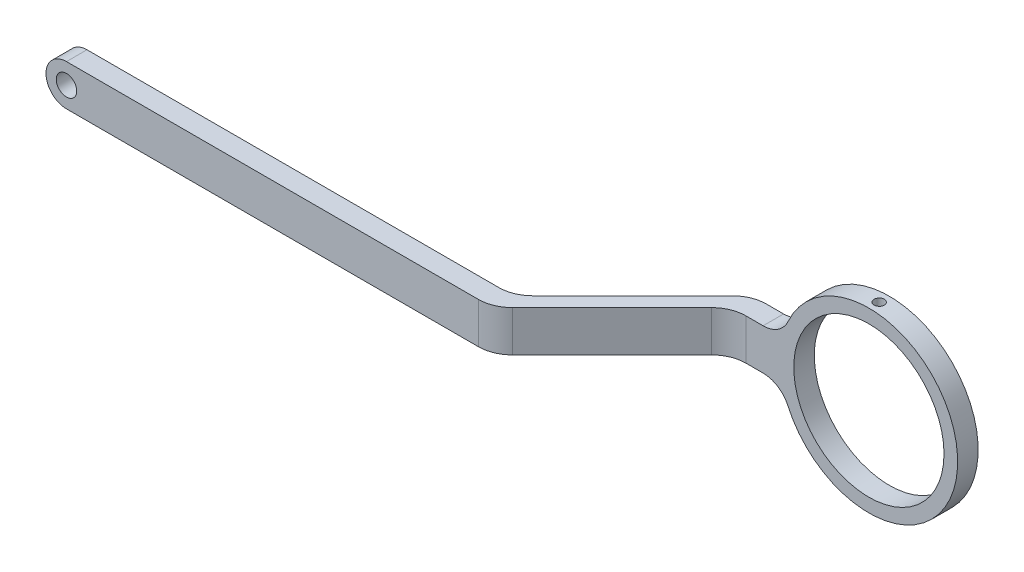
SolidWorks part; units mm, degrees
ref_plane "Front Plane" through (0, 0, 0) normal (0, 0, 1) x (1, 0, 0)
ref_plane "Top Plane" through (0, 0, 0) normal (0, 1, 0) x (1, 0, 0)
ref_plane "Right Plane" through (0, 0, 0) normal (1, 0, 0) x (0, 0, -1)
sketch "Sketch1" plane through (0, 0, 0) normal (0, 1, 0) x (1, 0, 0)
  line L0 (-830.58, 0) -> (830.58, 0) construction
  line L1 (830.58, 38.1) -> (830.58, 444.5) construction
  line L2 (830.58, 444.5) -> (1275.08, 444.5) construction
  line L3 (1275.08, 444.5) -> (2115.82, 444.5) construction
  line L4 (830.58, 38.1) -> (1275.08, 482.6)
  line L5 (-830.58, -38.1) -> (830.58, -38.1)
  line L6 (-830.58, -38.1) -> (-830.58, 38.1)
  line L7 (-830.58, 38.1) -> (830.58, 38.1)
  line L9 (-830.58, -38.1) -> (830.58, 38.1) construction
  line L10 (-830.58, 38.1) -> (830.58, -38.1) construction
  line L11 (1275.08, 406.4) -> (2115.82, 406.4)
  line L13 (1275.08, 482.6) -> (2115.82, 482.6)
  line L14 (2115.82, 406.4) -> (2115.82, 482.6)
  line L15 (1275.08, 406.4) -> (2115.82, 482.6) construction
  line L16 (1275.08, 482.6) -> (2115.82, 406.4) construction
  line L17 (830.58, -38.1) -> (1275.08, 406.4)
  point P4 (0, 0)
  point P8 (0, 0)
  point P13 (1695.45, 444.5)
  dimension "D1" = 830.58
  dimension "D2" = 1661.16
  dimension "D3" = 444.5
  dimension "D4" = 444.5
  dimension "D5" = 840.74
  dimension "D6" = 38.1
  dimension "D7" = 1661.16
  dimension "D8" = 76.2
  dimension "D9" = 840.74
  dimension "D11" = 38.1
extrude "Boss-Extrude1" add sketch "Sketch1" along normal mid plane 152.4
fillet "Fillet1" radius 127 4 edges at (1275.08, 0, -406.4) (1275.08, 0, -482.6) (830.58, 0, -38.1) (830.58, 0, 38.1)
sketch "Sketch2" plane through (0, 0, 38.1) normal (0, 0, 1) x (1, 0, 0)
  line L0 (-830.58, 76.2) -> (-830.58, -76.2) construction
  line L1 (-754.38, 76.2) -> (-830.58, 76.2)
  line L2 (-830.58, 76.2) -> (-830.58, -76.2)
  line L3 (-830.58, -76.2) -> (-754.38, -76.2)
  circle A0 centre (-754.38, 0) radius 76.2
  point P2 (-830.58, 0)
  point P3 (-830.58, 0)
  line M1 (-830.58, -76.2) -> (777.9749, -76.2)
  line M3 (777.9749, 76.2) -> (-830.58, 76.2)
  line M4 (-830.58, 76.2) -> (-830.58, -76.2)
  dimension "D1" = 152.4
extrude "Cut-Extrude1" cut sketch "Sketch2" against normal blind 152.4 contours A0 M3 M4 | A0 L2 M1
sketch "Sketch3" plane through (0, 0, 38.1) normal (0, 0, 1) x (1, 0, 0)
  line L0 (-754.38, 76.2) -> (-754.38, -76.2) construction
  circle A0 centre (-754.38, 0) radius 38.1
  dimension "D1" = 76.2
extrude "Cut-Extrude2" cut sketch "Sketch3" against normal blind 152.4
sketch "Sketch4" plane through (0, 0, -406.4) normal (0, 0, 1) x (1, 0, 0)
  line L0 (-754.38, 0) -> (1785.62, 0) construction
  line L1 (-754.38, 0) -> (-754.38, 38.1) construction
  circle A0 centre (1785.62, 0) radius 330.2
  circle A1 centre (1785.62, 0) radius 279.4
  circle A2 centre (-754.38, 0) radius 38.1 construction
  dimension "D2" = 660.4
  dimension "D3" = 558.8
  dimension "D1" = 2540
extrude "Boss-Extrude2" add sketch "Sketch4" against normal blind 76.2
sketch "Sketch5" plane through (0, 0, -406.4) normal (0, 0, 1) x (1, 0, 0)
  line L0 (2106.9074, 76.2) -> (2115.82, 76.2)
  line L1 (2115.82, 76.2) -> (2115.82, -76.2)
  line L2 (2115.82, -76.2) -> (2106.9074, -76.2)
  circle A0 centre (1785.62, 0) radius 279.4
  arc A1 (2106.9074, -76.2) -> (2106.9074, 76.2) centre (1785.62, 0) ccw
  line M2 (1516.8117, -76.2) -> (2054.4283, -76.2)
  line M3 (2054.4283, 76.2) -> (1516.8117, 76.2)
  line M7 (2106.9074, -76.2) -> (2115.82, -76.2)
  line M8 (2115.82, -76.2) -> (2115.82, 76.2)
  line M9 (2115.82, 76.2) -> (2106.9074, 76.2)
  dimension "D1" = 660.4
extrude "Cut-Extrude3" cut sketch "Sketch5" against normal blind 76.2 contours A0 M3 M2 | A1 L1 M9 | A1 M7 M8
fillet "Fillet2" radius 101.6 2 edges at (1464.3326, -76.2, -444.5) (1464.3326, 76.2, -444.5)
sketch "Sketch7" plane through (0, 0, -406.4) normal (0, 0, 1) x (1, 0, 0)
  line L0 (-754.38, 0) -> (1785.62, 0) construction
  line L1 (1785.62, 0) -> (1785.62, 330.2) construction
  dimension "D1" = 2540
sketch "Sketch9" plane through (0, 0, 0) normal (0, 1, 0) x (1, 0, 0)
  line L0 (1785.62, 406.4) -> (1785.62, 482.6) construction
  line L1 (-754.38, 406.4) -> (1785.62, 406.4) construction
  line L2 (2065.02, 482.6) -> (1506.22, 482.6) construction
  circle A0 centre (1785.62, 444.5) radius 19.05
  dimension "D1" = 38.1
extrude "Cut-Extrude4" cut sketch "Sketch9" along normal through all
